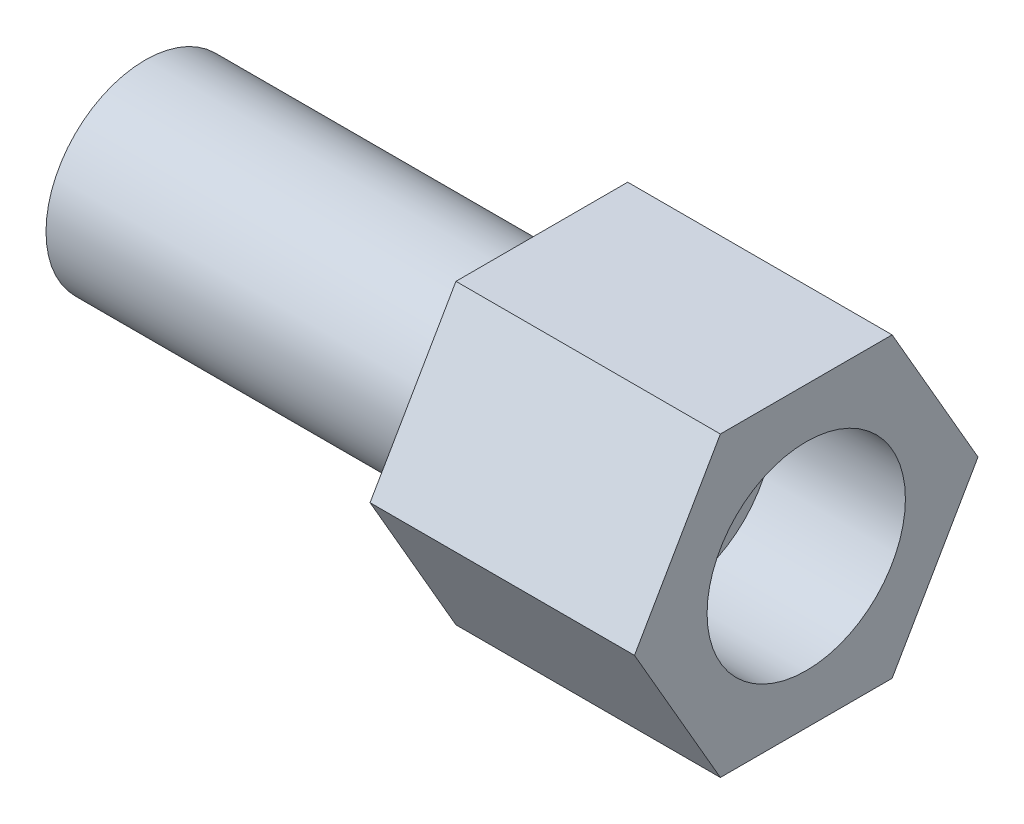
SolidWorks part; units mm, degrees
ref_plane "前视基准面" through (0, 0, 0) normal (0, 0, 1) x (1, 0, 0)
ref_plane "上视基准面" through (0, 0, 0) normal (0, 1, 0) x (1, 0, 0)
ref_plane "右视基准面" through (0, 0, 0) normal (1, 0, 0) x (0, 0, -1)
other "Configuration Table"
sketch "草图1" plane through (0, 0, 0) normal (1, 0, 0) x (0, 0, -1)
  circle A0 centre (0, 0) radius 1.5
  dimension "D1" = 3
extrude "凸台-拉伸1" add sketch "草图1" along normal blind 6
sketch "草图2" plane through (6, 0, 0) normal (1, 0, 0) x (0, 0, -1)
  line L1 (2.5981, 0) -> (1.299, 2.25)
  line L2 (1.299, 2.25) -> (-1.299, 2.25)
  line L3 (-1.299, 2.25) -> (-2.5981, 0)
  line L4 (-2.5981, 0) -> (-1.299, -2.25)
  line L5 (-1.299, -2.25) -> (1.299, -2.25)
  line L6 (1.299, -2.25) -> (2.5981, 0)
  circle A0 centre (0, 0) radius 2.25 construction
  dimension "D1" = 4.5
extrude "凸台-拉伸2" add sketch "草图2" along normal blind 4
sketch "草图3" plane through (10, 0, 0) normal (1, 0, 0) x (0, 0, -1)
  circle A0 centre (0, 0) radius 1.5
  dimension "D1" = 3
sketch "草图4" plane through (10, 0, 0) normal (1, 0, 0) x (0, 0, -1)
  circle A0 centre (0, 0) radius 1.5
extrude "切除-拉伸1" cut sketch "草图4" against normal blind 2
